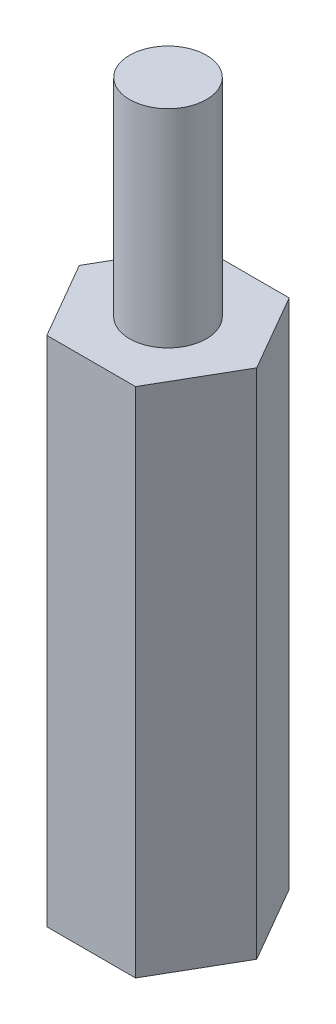
SolidWorks part; units mm, degrees
ref_plane "Front Plane" through (0, 0, 0) normal (0, 0, 1) x (1, 0, 0)
ref_plane "Top Plane" through (0, 0, 0) normal (0, 1, 0) x (1, 0, 0)
ref_plane "Right Plane" through (0, 0, 0) normal (1, 0, 0) x (0, 0, -1)
sketch "Sketch3" plane through (0, 0, 0) normal (0, 1, 0) x (1, 0, 0)
  line L1 (-3.4641, 0) -> (-1.7321, -3)
  line L2 (-1.7321, -3) -> (1.7321, -3)
  line L3 (1.7321, -3) -> (3.4641, 0)
  line L4 (3.4641, 0) -> (1.7321, 3)
  line L5 (1.7321, 3) -> (-1.7321, 3)
  line L6 (-1.7321, 3) -> (-3.4641, 0)
  circle A0 centre (0, 0) radius 3 construction
  dimension "D1" = 6
extrude "Boss-Extrude1" add sketch "Sketch3" along normal blind 20
sketch "Sketch5" plane through (0, 20, 0) normal (0, 1, 0) x (1, 0, 0)
  circle A0 centre (0, 0) radius 1.5
  dimension "D1" = 3
extrude "Boss-Extrude2" add sketch "Sketch5" along normal blind 8.0916
sketch "Sketch6" plane through (0, 0, 0) normal (0, -1, 0) x (1, 0, 0)
  circle A0 centre (0, 0) radius 1.5
extrude "Cut-Extrude1" cut sketch "Sketch6" against normal blind 4
